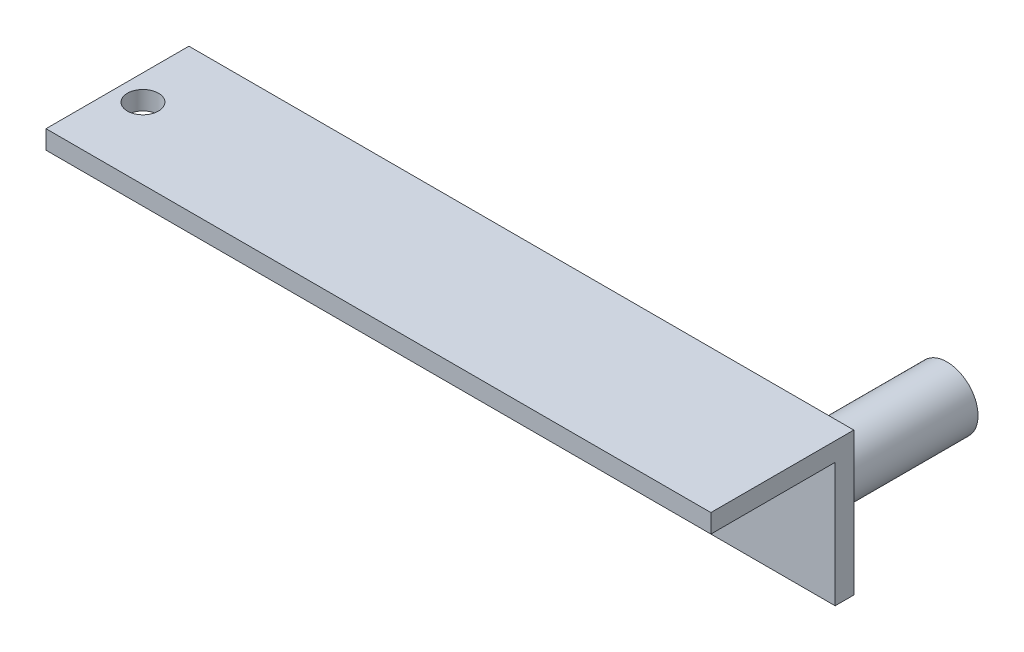
SolidWorks part; units mm, degrees
ref_plane "Front Plane" through (0, 0, 0) normal (0, 0, 1) x (1, 0, 0)
ref_plane "Top Plane" through (0, 0, 0) normal (0, 1, 0) x (1, 0, 0)
ref_plane "Right Plane" through (0, 0, 0) normal (1, 0, 0) x (0, 0, -1)
sketch "Sketch1" plane through (0, 0, 0) normal (0, 0, 1) x (1, 0, 0)
  line L1 (0, 0) -> (20, 0)
  line L2 (0, 0) -> (0, -23)
  line L3 (0, -23) -> (20, -23)
  line L4 (20, 0) -> (20, -23)
  dimension "D1" = 20
  dimension "D2" = 23
extrude "Boss-Extrude1" add sketch "Sketch1" along normal blind 3 contours L2 L3 L4 L1
sketch "Sketch2" plane through (0, 0, 3) normal (0, 0, 1) x (1, 0, 0)
  line L0 (20, 0) -> (20, -23) construction
  line L1 (0, 0) -> (20, 0)
  line L2 (0, 0) -> (0, -3)
  line L3 (0, -3) -> (20, -3)
  line L4 (20, 0) -> (20, -3)
  dimension "D1" = 3
extrude "Boss-Extrude2" add sketch "Sketch2" along normal blind 20
sketch "Sketch3" plane through (0, 0, 0) normal (0, 0, -1) x (-1, 0, 0)
  line L0 (0, -23) -> (-20, -23) construction
  line L3 (0, 0) -> (0, -23) construction
  circle A0 centre (-10, -13) radius 5
  dimension "D1" = 10
  dimension "D2" = 10
  dimension "D3" = 10
extrude "Boss-Extrude3" add sketch "Sketch3" along normal blind 25
sketch "Sketch4" plane through (0, 0, -25) normal (0, 0, -1) x (-1, 0, 0)
  line L0 (0, 0) -> (0, -23) construction
  line L2 (0, -23) -> (-20, -23) construction
  circle A0 centre (-10, -13) radius 3
  dimension "D1" = 6
  dimension "D2" = 10
  dimension "D3" = 10
extrude "Cut-Extrude1" cut sketch "Sketch4" against normal blind 25
sketch "Sketch5" plane through (0, 0, 0) normal (-1, 0, 0) x (0, 0, 1)
  line L1 (0, 0) -> (23, 0)
  line L2 (0, 0) -> (0, -3)
  line L3 (0, -3) -> (23, -3)
  line L4 (23, 0) -> (23, -3)
extrude "Boss-Extrude4" add sketch "Sketch5" along normal blind 87
sketch "Sketch6" plane through (0, 0, 0) normal (0, 1, 0) x (1, 0, 0)
  line L0 (-87, 0) -> (20, 0) construction
  circle A0 centre (-82.9, -11.5) radius 2.5
  dimension "D1" = 5
  dimension "D2" = 82.9
  dimension "D3" = 11.5
extrude "Cut-Extrude2" cut sketch "Sketch6" against normal blind 3
